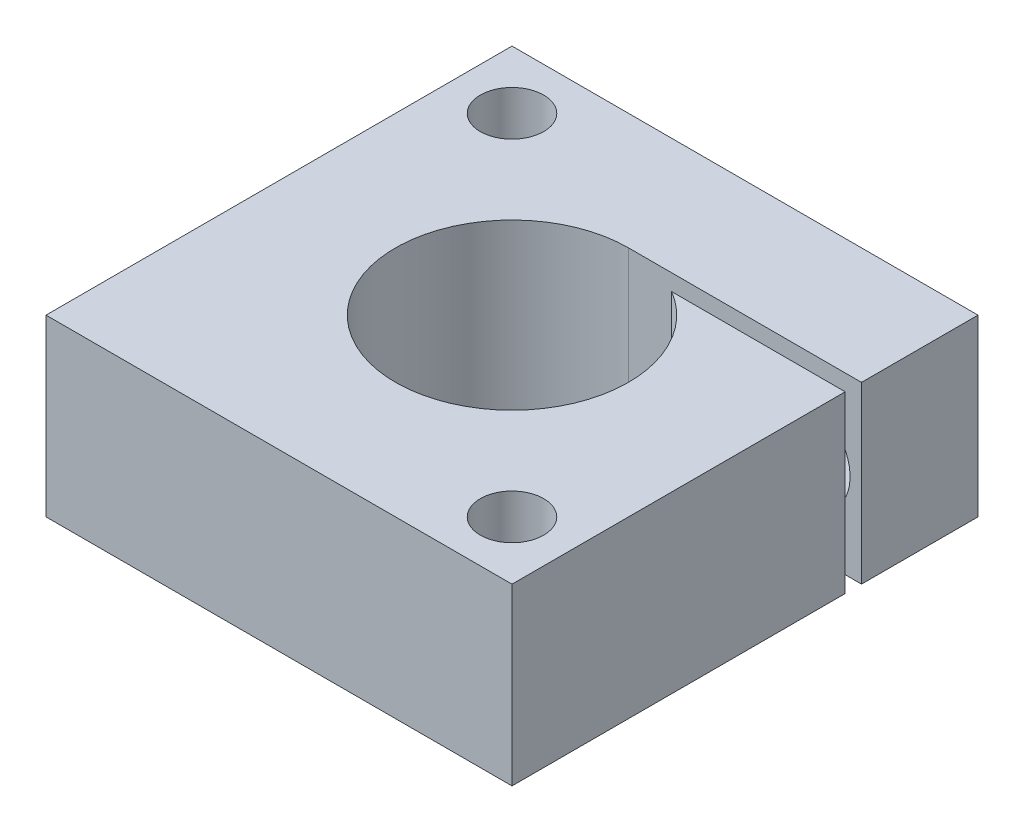
SolidWorks part; units mm, degrees
ref_plane "Front Plane" through (0, 0, 0) normal (0, 0, 1) x (1, 0, 0)
ref_plane "Top Plane" through (0, 0, 0) normal (0, 1, 0) x (1, 0, 0)
ref_plane "Right Plane" through (0, 0, 0) normal (1, 0, 0) x (0, 0, -1)
sketch "Sketch1" plane through (0, 0, 0) normal (0, 1, 0) x (1, 0, 0)
  line L0 (1.5006, 8.4813) -> (1.5006, -9.6797)
  line L1 (-11.1994, 9.3703) -> (1.5006, 9.3703)
  line L2 (-23.8994, 15.7203) -> (1.5006, 15.7203)
  line L3 (-23.8994, 15.7203) -> (-23.8994, -9.6797)
  line L4 (-23.8994, -9.6797) -> (1.5006, -9.6797)
  line L5 (1.5006, 15.7203) -> (1.5006, 9.3703)
  line L7 (-7.959, 8.4813) -> (1.5006, 8.4813)
  arc A0 (-11.1994, 9.3703) -> (-7.959, 8.4813) centre (-11.1994, 3.0203) ccw
  dimension "D3" = 12.7
  dimension "D4" = 12.7
  dimension "D5" = 12.7
  dimension "D1" = 25.4
  dimension "D2" = 25.4
  dimension "D6" = 0.889
extrude "Boss-Extrude1" add sketch "Sketch1" along normal blind 9.525
hole_wizard "#8-32 Tapped Hole1" positions "Sketch3" profile "Sketch2" tap size "#8-32" standard "ANSI Inch" end condition through all
sketch "Sketch3" plane through (0, 9.525, 0) normal (0, 1, 0) x (1, 0, 0)
  arc A0 (-11.1994, 9.3703) -> (-7.959, 8.4813) centre (-11.1994, 3.0203) ccw construction
  point P0 (-20.7244, 12.5453)
  point P2 (-1.6744, -6.5047)
  dimension "D3" = 9.525
  dimension "D4" = 9.525
  dimension "D1" = 9.525
  dimension "D2" = 9.525
sketch "Sketch2" plane through (-20.7244, 9.525, -12.5453) normal (1, 0, 0) x (0, 0, 1)
  line L0 (0, 0) -> (0, 9.525)
  line L1 (0, 9.525) -> (1.7272, 9.525)
  line L2 (1.7272, 9.525) -> (1.7272, 0)
  line L5 (1.7272, 0) -> (0, 0)
  line L11 (0, -6.35) -> (0, 107.95) construction
  dimension "Thru Tap Drill Dia." = 3.4544
  dimension "Thru Tap Drill Depth" = 9.525
cosmetic thread "Hole Thread1" parameters "D2"=4.1656
cosmetic thread "Hole Thread2" parameters "D2"=4.1656
hole_wizard "#10-24 Tapped Hole1" positions "Sketch5" profile "Sketch4" tap size "#10-24" standard "ANSI Inch"
sketch "Sketch5" plane through (0, 0, -8.4813) normal (0, 0, -1) x (-1, 0, 0)
  line L0 (-1.5006, 9.525) -> (-1.5006, 0) construction
  line L2 (-1.5006, 9.525) -> (23.8994, 9.525) construction
  point P0 (1.6744, 4.7625)
  dimension "D1" = 3.175
  dimension "D2" = 4.7625
sketch "Sketch4" plane through (-1.6744, 4.7625, -8.4813) normal (1, 0, 0) x (0, 1, 0)
  line L0 (0, 0) -> (0, 12.3168)
  line L1 (0, 12.3168) -> (1.8986, 11.176)
  line L2 (1.8986, 11.176) -> (1.8986, 0)
  line L5 (1.8986, 0) -> (0, 0)
  line L10 (0, 12.3168) -> (-1.8987, 11.176) construction
  line L11 (0, -6.35) -> (0, 107.95) construction
  dimension "Tap Drill Dia." = 3.7973
  dimension "Tap Drill Depth" = 11.176
  dimension "Drill Angle" = 118
cosmetic thread "Hole Thread3" parameters "D1"=8.89, "D2"=4.826
hole_wizard "#10 Clearance Hole1" positions "Sketch7" profile "Sketch8" hole size "#10" standard "ANSI Inch"
sketch "Sketch7" plane through (0, 0, -15.7203) normal (0, 0, -1) x (-1, 0, 0)
  line L0 (-1.5006, 0) -> (23.8994, 0) construction
  line L1 (-1.5006, 9.525) -> (-1.5006, 0) construction
  point P0 (1.6744, 4.7625)
  dimension "D1" = 4.7625
  dimension "D2" = 3.175
sketch "Sketch8" plane through (-1.6744, 4.7625, -15.7203) normal (1, 0, 0) x (0, 1, 0)
  line L0 (0, 0) -> (0, 6.35)
  line L1 (0, 6.35) -> (2.5527, 6.35)
  line L2 (2.5527, 6.35) -> (2.5527, 0)
  line L5 (2.5527, 0) -> (0, 0)
  line L11 (0, -6.35) -> (0, 107.95) construction
  dimension "Thru Hole Dia." = 5.1054
  dimension "Thru Hole Depth" = 6.35
